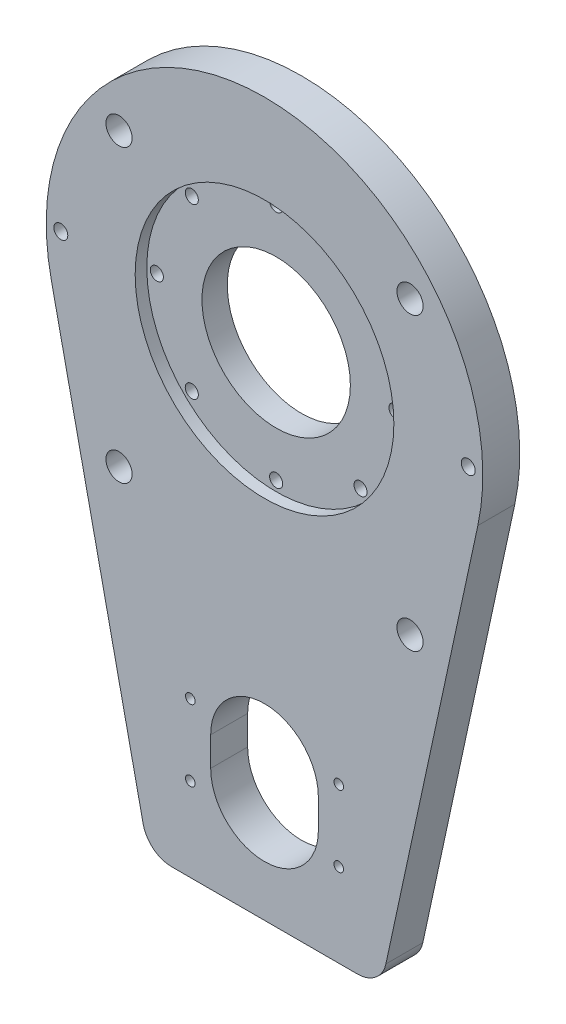
SolidWorks part; units mm, degrees
material "6061 Alloy"
ref_plane "Front" through (0, 0, 0) normal (0, 0, 1) x (1, 0, 0)
ref_plane "Top" through (0, 0, 0) normal (0, 1, 0) x (1, 0, 0)
ref_plane "Right" through (0, 0, 0) normal (1, 0, 0) x (0, 0, -1)
ref_plane "Plane1" through (0, 0, 12.7) normal (0, 0, 1) x (1, 0, 0)
sketch "Sketch1" plane through (0, 0, 12.7) normal (0, 0, 1) x (1, 0, 0)
  line L0 (40, -170) -> (73.3084, -15.8392)
  line L1 (-73.3084, -15.8392) -> (-40, -170)
  line L2 (-40, -170) -> (40, -170)
  arc A0 (73.3084, -15.8392) -> (-73.3084, -15.8392) centre (0, 0) ccw
extrude "Boss-Extrude1" add sketch "Sketch1" against normal blind 12.7
sketch "Sketch2" plane through (0, 0, 0) normal (0, 0, -1) x (-1, 0, 0)
  line L0 (-18.5, -124) -> (-18.5, -134)
  line L1 (18.5, -134) -> (18.5, -124)
  arc A0 (-18.5, -134) -> (18.5, -134) centre (0, -134) ccw
  arc A1 (18.5, -124) -> (-18.5, -124) centre (0, -124) ccw
  dimension "D1" = 18.5
  dimension "D2" = 10
  dimension "D3" = 124
extrude "Cut-Extrude1" cut sketch "Sketch2" against normal through all
hole_wizard "M8 Clearance Hole1" positions "Sketch4" profile "Sketch3" hole size "M8" standard "ANSI Metric"
sketch "Sketch4" plane through (0, 0, 0) normal (0, 0, -1) x (-1, 0, 0)
  point P0 (-50, -60)
  point P1 (50, -60)
  point P2 (-50, 40)
  point P3 (50, 40)
sketch "Sketch3" plane through (50, -60, 0) normal (1, 0, 0) x (0, 1, 0)
  line L0 (0, 0) -> (0, 28.1039)
  line L1 (0, 28.1039) -> (4.5, 25.4)
  line L2 (4.5, 25.4) -> (4.5, 0)
  line L5 (4.5, 0) -> (0, 0)
  line L10 (0, 28.1039) -> (-4.5, 25.4) construction
  line L11 (0, -6.35) -> (0, 107.95) construction
  dimension "Hole Dia." = 9
  dimension "Hole Depth" = 25.4
  dimension "Drill Angle" = 118
hole_wizard "M4x0.7 Tapped Hole1" positions "Sketch6" profile "Sketch5" tap size "M4x0.7" standard "ANSI Metric" end condition through all
sketch "Sketch6" plane through (0, 0, 12.7) normal (0, 0, 1) x (1, 0, 0)
  point P0 (-25.5, -116.75)
  point P1 (-25.5, -141.25)
  point P2 (25.5, -116.75)
  point P3 (25.5, -141.25)
sketch "Sketch5" plane through (-25.5, -116.75, 12.7) normal (1, 0, 0) x (0, -1, 0)
  line L0 (0, 0) -> (0, 12.7)
  line L1 (0, 12.7) -> (1.65, 12.7)
  line L2 (1.65, 12.7) -> (1.65, 0)
  line L5 (1.65, 0) -> (0, 0)
  line L11 (0, -6.35) -> (0, 107.95) construction
  dimension "Thru Tap Drill Dia." = 3.3
  dimension "Thru Tap Drill Depth" = 12.7
hole_wizard "M4 Clearance Hole1" positions "Sketch8" profile "Sketch7" hole size "M4" standard "ANSI Metric" end condition through all
sketch "Sketch8" plane through (0, 0, 12.7) normal (0, 0, 1) x (1, 0, 0)
  point P0 (70, 0)
  point P1 (-70, 0)
sketch "Sketch7" plane through (70, 0, 12.7) normal (1, 0, 0) x (0, -1, 0)
  line L0 (0, 0) -> (0, 12.7)
  line L1 (0, 12.7) -> (2.4, 12.7)
  line L2 (2.4, 12.7) -> (2.4, 0)
  line L5 (2.4, 0) -> (0, 0)
  line L11 (0, -6.35) -> (0, 107.95) construction
  dimension "Thru Hole Dia." = 4.8
  dimension "Thru Hole Depth" = 12.7
hole_wizard "Hole2" positions "Sketch10" profile "Sketch9" legacy
sketch "Sketch10" plane through (0, 0, 12.7) normal (0, 0, 1) x (1, 0, 0)
  point P0 (0, 0)
sketch "Sketch9" plane through (0, 0, 12.7) normal (1, 0, 0) x (0, -1, 0)
  line L0 (0, 0) -> (0, 12.7)
  line L1 (0, 12.7) -> (25.5, 12.7)
  line L2 (25.5, 12.7) -> (25.5, 4)
  line L3 (25.5, 4) -> (44.45, 4)
  line L4 (44.45, 4) -> (44.45, 0)
  line L5 (44.45, 0) -> (0, 0)
  line L6 (0, 110) -> (0, -10) construction
  dimension "Diameter" = 51
  dimension "Depth" = 12.7
  dimension "C-Bore Diameter" = 88.9
  dimension "C-Bore Depth" = 4
hole_wizard "CBORE for M4 SHCS1" positions "Sketch12" profile "Sketch11" counterbore size "M4" standard "ANSI Metric" end condition through all
sketch "Sketch12" plane through (0, 0, 0) normal (0, 0, -1) x (-1, 0, 0)
  point P0 (28.9914, 28.9914)
  point P1 (41, 0)
  point P2 (28.9914, -28.9914)
  point P3 (0, -41)
  point P4 (-28.9914, -28.9914)
  point P5 (-41, 0)
  point P6 (-28.9914, 28.9914)
  point P7 (0, 41)
sketch "Sketch11" plane through (-28.9914, 28.9914, 0) normal (1, 0, 0) x (0, 1, 0)
  line L0 (0, 0) -> (0, 12.7)
  line L1 (0, 12.7) -> (2.25, 12.7)
  line L3 (2.25, 12.7) -> (2.25, 4)
  line L4 (2.25, 4) -> (4, 4)
  line L5 (4, 4) -> (4, 0)
  line L7 (4, 0) -> (0, 0)
  line L11 (0, -6.35) -> (0, 107.95) construction
  dimension "Thru Hole Dia." = 4.5
  dimension "Thru Hole Depth" = 12.7
  dimension "C'Bore Dia." = 8
  dimension "C'Bore Depth" = 4
fillet "Fillet1" radius 10 2 edges at (-40, -170, 6.35) (40, -170, 6.35)
